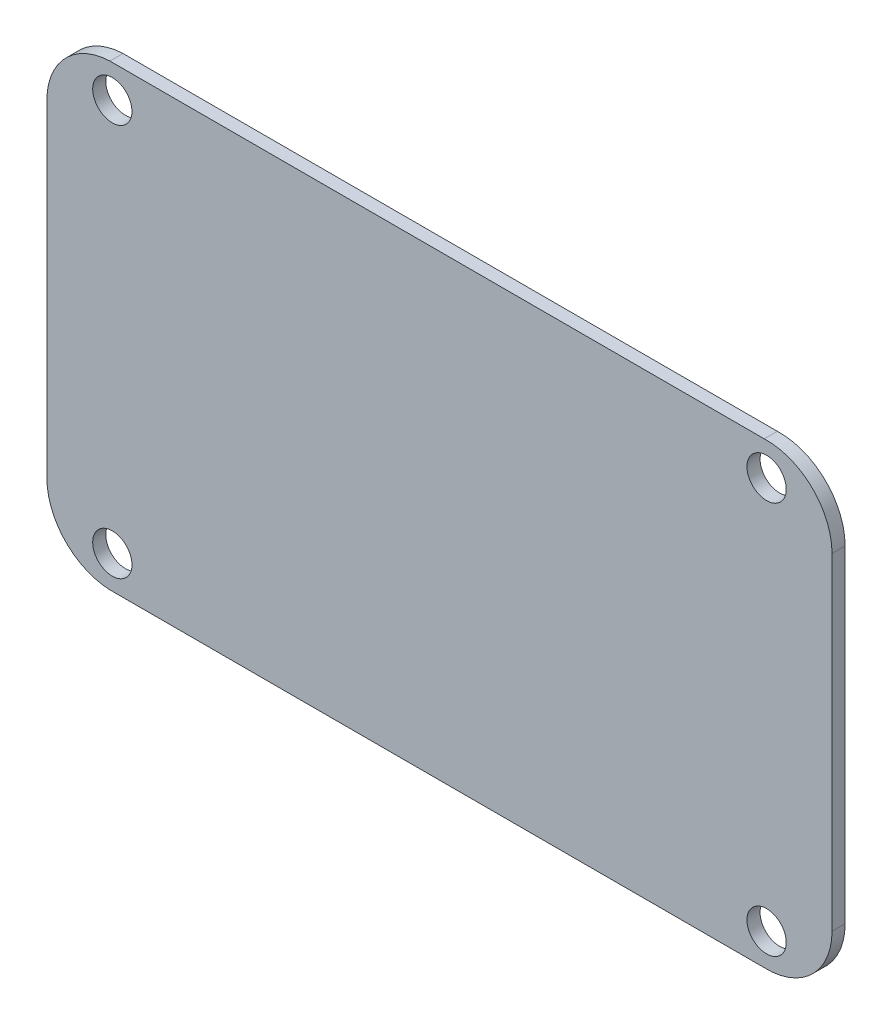
SolidWorks part; units mm, degrees
material "1.0045 (S355JR)"
ref_plane "Plan de face" through (0, 0, 0) normal (0, 0, 1) x (1, 0, 0)
ref_plane "Plan de dessus" through (0, 0, 0) normal (0, 1, 0) x (1, 0, 0)
ref_plane "Plan de droite" through (0, 0, 0) normal (1, 0, 0) x (0, 0, -1)
sketch "Esquisse1" plane through (0, 0, 0) normal (0, 0, 1) x (1, 0, 0)
  line L0 (-50.3628, -35) -> (49.6372, -35)
  line L1 (60, -25) -> (60, 25)
  line L2 (49.6372, 35) -> (-50.3628, 35)
  line L3 (-60, 25) -> (-60, -25)
  arc A0 (-60, -25) -> (-50.3628, -35) centre (-50, -25.0066) ccw
  arc A1 (49.6372, -35) -> (60, -25) centre (50, -25.0066) ccw
  arc A2 (60, 25) -> (49.6372, 35) centre (50, 25.0066) ccw
  arc A3 (-50.3628, 35) -> (-60, 25) centre (-50, 25.0066) ccw
  dimension "D1" = 70
  dimension "D2" = 35
  dimension "D3" = 120
  dimension "D4" = 60
extrude "Boss.-Extru.1" add sketch "Esquisse1" along normal blind 2
sketch "Esquisse2" plane through (0, 0, 2) normal (0, 0, 1) x (1, 0, 0)
  line L0 (0, 0) -> (0, 17.7365) construction
  line L1 (0, 0) -> (9.2005, 0) construction
  line L2 (49.6372, 35) -> (-50.3628, 35) construction
  line L3 (-60, 25) -> (-60, -25) construction
  circle A0 centre (-50, 30) radius 3
  circle A1 centre (50, 30) radius 3
  circle A2 centre (50, -30) radius 3
  circle A3 centre (-50, -30) radius 3
  dimension "D1" = 6
  dimension "D2" = 5
  dimension "D3" = 10
extrude "Enlèv. mat.-Extru.1" cut sketch "Esquisse2" against normal blind 10
